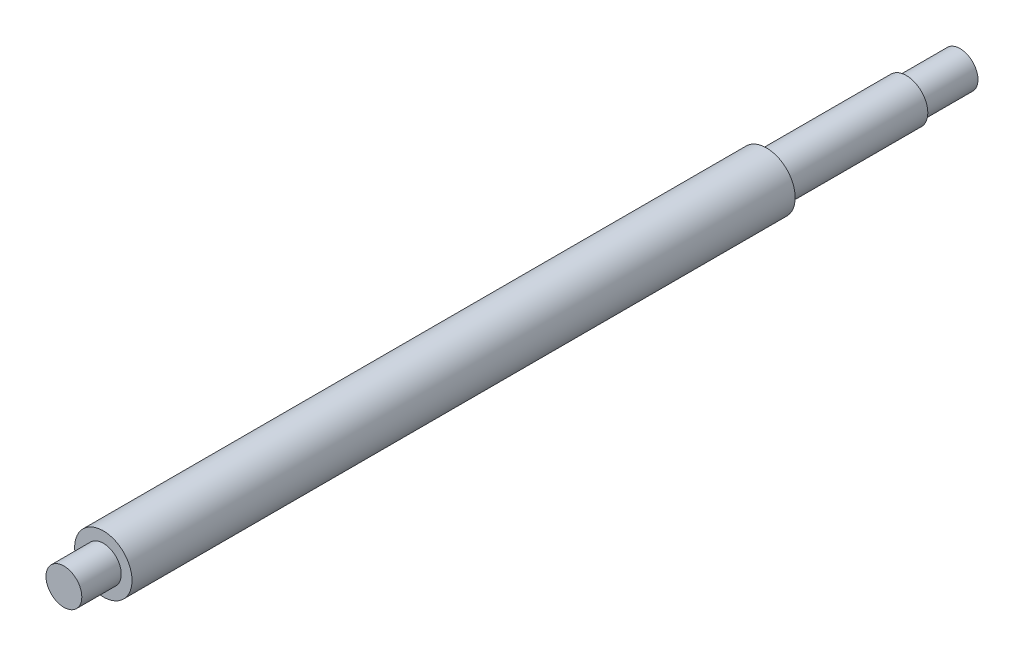
SolidWorks part; units mm, degrees
ref_plane "Plan de face" through (0, 0, 0) normal (0, 0, 1) x (1, 0, 0)
ref_plane "Plan de dessus" through (0, 0, 0) normal (0, 1, 0) x (1, 0, 0)
ref_plane "Plan de droite" through (0, 0, 0) normal (1, 0, 0) x (0, 0, -1)
sketch "Esquisse1" plane through (0, 0, 0) normal (0, 0, 1) x (1, 0, 0)
  circle A0 centre (0, 0) radius 5
  dimension "D1" = 10
extrude "Boss.-Extru.1" add sketch "Esquisse1" along normal blind 15
sketch "Esquisse2" plane through (0, 0, 15) normal (0, 0, 1) x (1, 0, 0)
  circle A0 centre (0, 0) radius 6
  dimension "D1" = 12
extrude "Boss.-Extru.2" add sketch "Esquisse2" along normal blind 39
sketch "Esquisse3" plane through (0, 0, 54) normal (0, 0, 1) x (1, 0, 0)
  circle A0 centre (0, 0) radius 8
  dimension "D1" = 16
extrude "Boss.-Extru.3" add sketch "Esquisse3" along normal blind 185
sketch "Esquisse4" plane through (0, 0, 239) normal (0, 0, 1) x (1, 0, 0)
  circle A0 centre (0, 0) radius 5
  dimension "D1" = 10
extrude "Boss.-Extru.4" add sketch "Esquisse4" along normal blind 11
